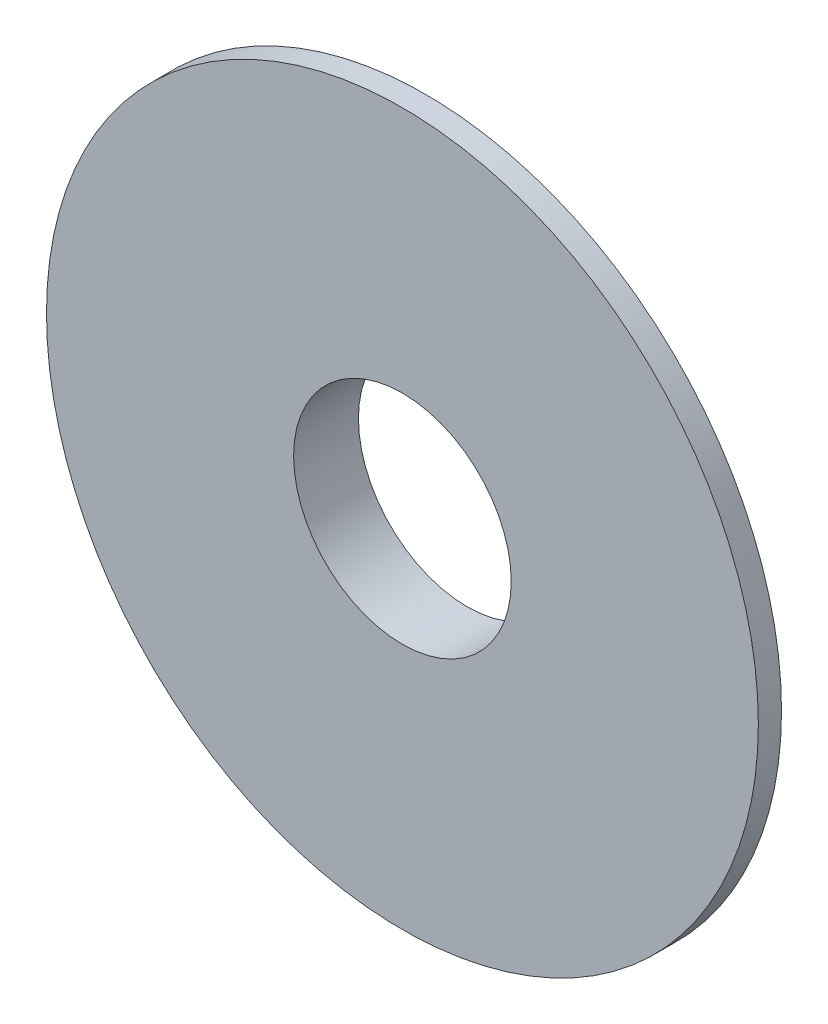
SolidWorks part; units mm, degrees
ref_plane "Спереди" through (0, 0, 0) normal (0, 0, 1) x (1, 0, 0)
ref_plane "Сверху" through (0, 0, 0) normal (0, 1, 0) x (1, 0, 0)
ref_plane "Справа" through (0, 0, 0) normal (1, 0, 0) x (0, 0, -1)
sketch "Эскиз1" plane through (0, 0, 0) normal (0, 0, 1) x (1, 0, 0)
  circle A0 centre (0, 0) radius 76.8769
  circle A1 centre (0, 0) radius 23.5
extrude "Cover_web" add sketch "Эскиз1" along normal blind 5 from offset 35
sketch "Эскиз2" plane through (0, 0, 0) normal (0, 0, 1) x (1, 0, 0)
  circle A0 centre (0, 0) radius 27.5
  circle A1 centre (0, 0) radius 23.5
extrude "Bearing_boss" add sketch "Эскиз2" along normal blind 14 from offset 26
